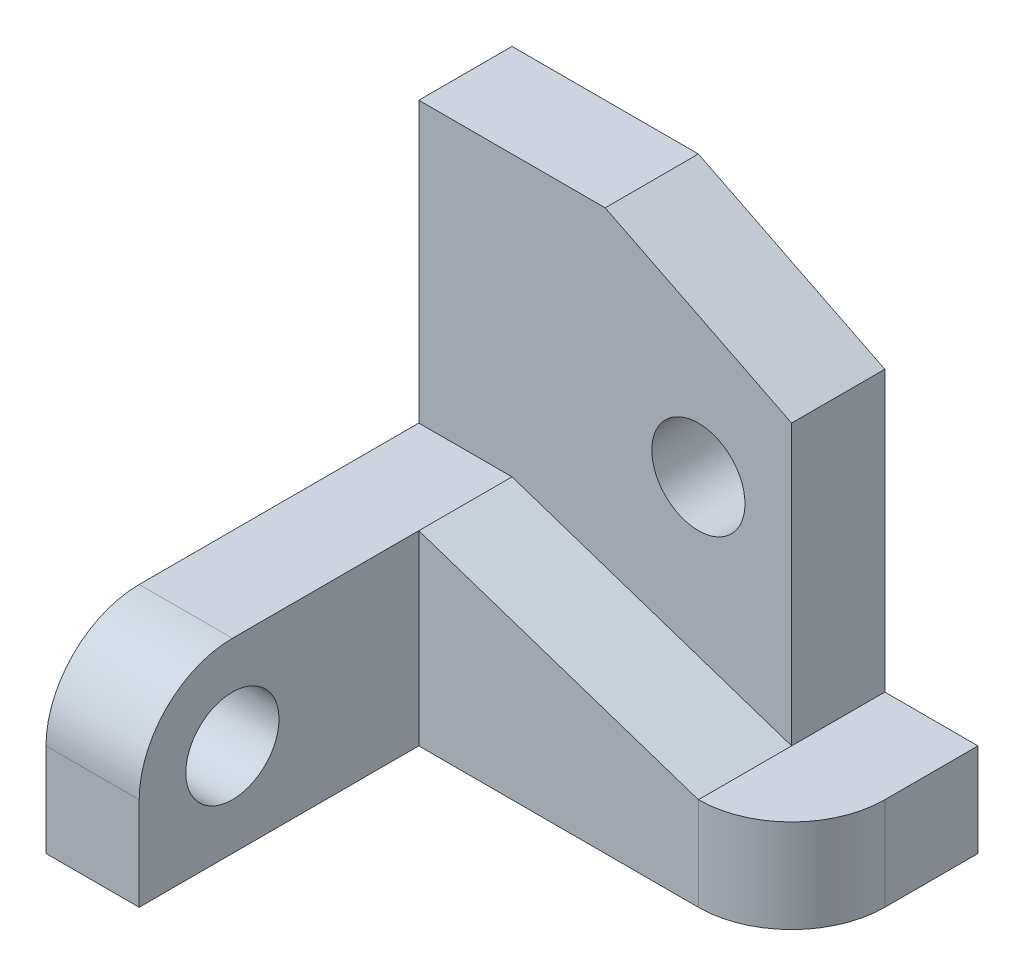
SolidWorks part; units mm, degrees
ref_plane "前基準面" through (0, 0, 0) normal (0, 0, 1) x (1, 0, 0)
ref_plane "上基準面" through (0, 0, 0) normal (0, 1, 0) x (1, 0, 0)
ref_plane "右基準面" through (0, 0, 0) normal (1, 0, 0) x (0, 0, -1)
sketch "草圖1" plane through (0, 0, 0) normal (0, 0, 1) x (1, 0, 0)
  line L0 (-10, 25) -> (0, 20)
  line L1 (0, 0) -> (-20, 0)
  line L2 (0, 0) -> (0, 20)
  line L3 (-10, 25) -> (-20, 25)
  line L4 (-20, 0) -> (-20, 25)
  circle A0 centre (-5, 15) radius 2.5
  dimension "D2" = 5
  dimension "D1" = 5
  dimension "D3" = 15
  dimension "D4" = 20
  dimension "D5" = 25
  dimension "D6" = 10
  dimension "D7" = 5
extrude "填料-伸長1" add sketch "草圖1" along normal blind 5
sketch "草圖2" plane through (0, 0, 5) normal (0, 0, 1) x (1, 0, 0)
  line L0 (-15, 10) -> (0, 5)
  line L1 (0, 0) -> (0, 20) construction
  line L2 (0, 5) -> (5, 5)
  line L3 (5, 5) -> (5, 0)
  line L4 (5, 0) -> (-15, 0)
  line L5 (-20, 0) -> (0, 0) construction
  line L6 (-15, 0) -> (-15, 10)
  line L7 (-20, 25) -> (-20, 0) construction
  dimension "D1" = 5
  dimension "D2" = 10
  dimension "D3" = 5
  dimension "D4" = 5
extrude "填料-伸長2" add sketch "草圖2" along normal blind 5
sketch "草圖3" plane through (-20, 0, 0) normal (-1, 0, 0) x (0, 0, 1)
  line L0 (0, 25) -> (0, 0) construction
  line L1 (5, 0) -> (25, 0)
  line L2 (5, 0) -> (5, 10)
  line L3 (5, 10) -> (25, 10)
  line L4 (25, 0) -> (25, 10)
  circle A0 centre (20, 5) radius 2.5
  dimension "D3" = 5
  dimension "D1" = 25
  dimension "D2" = 10
  dimension "D4" = 5
  dimension "D5" = 5
extrude "填料-伸長3" add sketch "草圖3" against normal up to surface (5 mm away) up to face at (-15, 5, 7.5)
fillet "圓角1" radius 5 1 edges at (-17.5, 10, 25)
sketch "草圖4" plane through (0, 0, 5) normal (0, 0, -1) x (-1, 0, 0)
  line L4 (-5, 0) -> (0, 0)
  line L5 (0, 0) -> (0, 5)
  line L6 (0, 5) -> (-5, 5)
  line L7 (-5, 5) -> (-5, 0)
  line L8 (-5, 0) -> (0, 0)
  line L9 (0, 0) -> (0, 5)
  line L10 (0, 5) -> (-5, 5)
  line L11 (-5, 5) -> (-5, 0)
  dimension "D1" = 0
extrude "填料-伸長4" add sketch "草圖4" along normal up to surface (5 mm away) up to face at (-10, 14, 0)
fillet "圓角2" radius 5 1 edges at (5, 2.5, 10)
